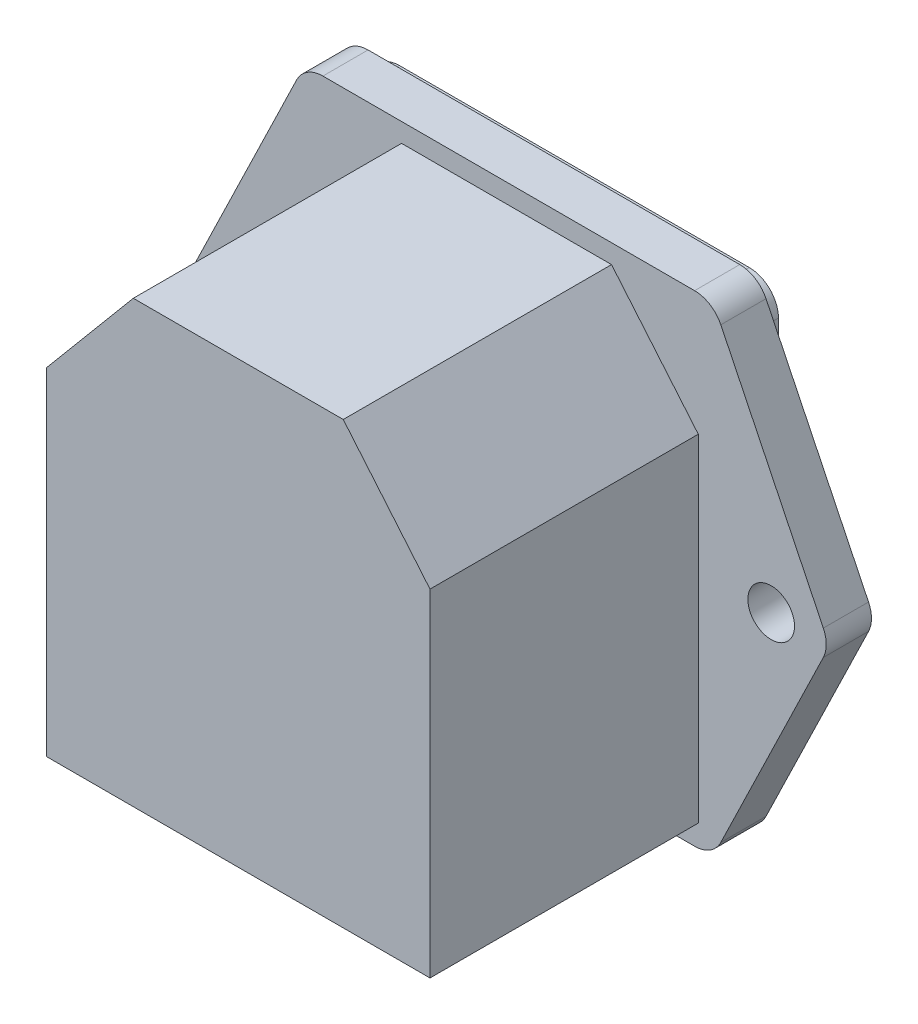
SolidWorks part; units mm, degrees
ref_plane "Front Plane" through (0, 0, 0) normal (0, 0, 1) x (1, 0, 0)
ref_plane "Top Plane" through (0, 0, 0) normal (0, 1, 0) x (1, 0, 0)
ref_plane "Right Plane" through (0, 0, 0) normal (1, 0, 0) x (0, 0, -1)
sketch "Sketch1" plane through (0, 0, 0) normal (0, 0, 1) x (1, 0, 0)
  line L1 (0, 0) -> (26.3, 0)
  line L2 (0, 0) -> (0, 30.2)
  line L3 (0, 30.2) -> (26.3, 30.2)
  line L4 (26.3, 0) -> (26.3, 30.2)
  dimension "D1" = 26.3
  dimension "D2" = 30.2
extrude "Boss-Extrude1" add sketch "Sketch1" along normal blind 21.5
sketch "Sketch2" plane through (0, 0, 21.5) normal (0, 0, 1) x (1, 0, 0)
  line L0 (0, 23.1) -> (26.3, 23.1)
  line L1 (0, 30.2) -> (0, 0) construction
  line L2 (26.3, 0) -> (26.3, 30.2) construction
  line L3 (26.3, 30.2) -> (0, 30.2) construction
  line L4 (13.15, 30.2) -> (13.15, 41.5338) construction
  line L5 (20.35, 30.2) -> (5.95, 30.2)
  line L6 (5.95, 30.2) -> (0, 23.1)
  line L7 (20.35, 30.2) -> (26.3, 23.1)
  line L9 (26.3, 23.1) -> (0, 23.1)
  line L10 (26.3, 23.1) -> (26.3, 30.2)
  line L11 (26.3, 30.2) -> (0, 30.2)
  line L12 (0, 23.1) -> (0, 30.2)
  line M7 (0, 30.2) -> (0, 0)
  line M9 (26.3, 0) -> (26.3, 30.2)
  line M10 (26.3, 30.2) -> (0, 30.2)
  dimension "D1" = 7.1
  dimension "D2" = 7.2
extrude "Cut-Extrude1" cut sketch "Sketch2" against normal blind 26 contours L6 M10 M7 | L7 M10 M9
sketch "Sketch3" plane through (0, 0, 0) normal (0, 0, -1) x (-1, 0, 0)
  line L0 (-26.3, 0) -> (-26.3, 23.1) construction
  line L1 (-35.3, -1.5) -> (8.7, -1.5)
  line L2 (-35.3, -1.5) -> (-35.3, 31.5)
  line L3 (-35.3, 31.5) -> (8.7, 31.5)
  line L4 (8.7, -1.5) -> (8.7, 31.5)
  line L5 (0, 0) -> (-26.3, 0) construction
  dimension "D1" = 33
  dimension "D2" = 44
  dimension "D3" = 9
  dimension "D4" = 1.5
extrude "Boss-Extrude2" add sketch "Sketch3" against normal blind 3.1
sketch "Sketch4" plane through (0, 0, 0) normal (0, 0, -1) x (-1, 0, 0)
  line L0 (-13.3, 31.5) -> (-13.3, 35.1997) construction
  line L1 (8.7, 31.5) -> (-35.3, 31.5) construction
  line L2 (0.7, 31.5) -> (-27.3, 31.5)
  line L3 (-35.3, 15) -> (-39.974, 15) construction
  line L4 (-35.3, 31.5) -> (-35.3, -1.5) construction
  line L5 (-27.3, 31.5) -> (-35.3, 15)
  line L6 (0.7, 31.5) -> (8.7, 15)
  line L7 (-27.3, -1.5) -> (-35.3, 15)
  line L8 (0.7, -1.5) -> (8.7, 15)
  line L9 (-13.3, -1.5) -> (-13.3, -5.1997) construction
  line L10 (0.7, -1.5) -> (-27.3, -1.5)
  line L12 (-35.3, 31.5) -> (8.7, 31.5)
  line L13 (-35.3, 31.5) -> (-35.3, -1.5)
  line L14 (-35.3, -1.5) -> (8.7, -1.5)
  line L15 (8.7, 31.5) -> (8.7, -1.5)
  line M6 (-35.3, 31.5) -> (-35.3, -1.5)
  line M7 (-35.3, -1.5) -> (8.7, -1.5)
  line M8 (8.7, -1.5) -> (8.7, 31.5)
  line M9 (8.7, 31.5) -> (-35.3, 31.5)
  dimension "D1" = 14
extrude "Cut-Extrude2" cut sketch "Sketch4" against normal blind 3.1 contours L5 M9 M6 | L6 M9 M8 | L8 M7 M8 | L7 M7 M6
fillet "Fillet1" radius 2 6 edges at (-0.7, -1.5, 1.55) (27.3, -1.5, 1.55) (27.3, 31.5, 1.55) (-0.7, 31.5, 1.55) (-8.7, 15, 1.55) (35.3, 15, 1.55)
sketch "Sketch5" plane through (0, 0, 0) normal (0, 0, -1) x (-1, 0, 0)
  line L0 (-13.3, 31.5) -> (-13.3, -1.5) construction
  line L1 (-0.553, 31.5) -> (-26.047, 31.5) construction
  line L2 (-26.047, -1.5) -> (-0.553, -1.5) construction
  line L4 (-35.0773, 15) -> (8.4773, 15) construction
  line L5 (-27.3, -0.25) -> (0.7, -0.25)
  line L6 (-27.3, -0.25) -> (-27.3, 30.25)
  line L7 (-27.3, 30.25) -> (0.7, 30.25)
  line L8 (0.7, -0.25) -> (0.7, 30.25)
  line L9 (-27.3, -0.25) -> (0.7, 30.25) construction
  line L10 (-27.3, 30.25) -> (0.7, -0.25) construction
  arc A0 (-34.8769, 15.8725) -> (-34.8769, 14.1275) centre (-33.0773, 15) ccw construction
  arc A1 (8.2769, 14.1275) -> (8.2769, 15.8725) centre (6.4773, 15) ccw construction
  point P14 (-13.3, 15)
  dimension "D1" = 28
  dimension "D2" = 30.5
extrude "Boss-Extrude3" add sketch "Sketch5" along normal blind 1.4
fillet "Fillet2" radius 2 4 edges at (-0.7, -0.25, -0.7) (27.3, -0.25, -0.7) (-0.7, 30.25, -0.7) (27.3, 30.25, -0.7)
sketch "Sketch6" plane through (0, 0, -1.4) normal (0, 0, -1) x (-1, 0, 0)
  line L0 (-27.3, 28.25) -> (-27.3, 1.75) construction
  line L1 (-1.3, 30.25) -> (-25.3, 30.25) construction
  line L2 (-25.3, 24.25) -> (-1.3, 24.25) construction
  line L3 (-25.3, 11.45) -> (-25.3, 28.45)
  line L4 (-25.3, 11.45) -> (-1.3, 11.45)
  line L5 (-25.3, 28.45) -> (-1.3, 28.45)
  line L6 (-1.3, 11.45) -> (-1.3, 28.45)
  line L7 (-1.3, 24.25) -> (-5.55, 28.45)
  line L8 (-25.3, 24.25) -> (-21.05, 28.45)
  line L9 (-13.3, 28.45) -> (-13.3, 32.8316) construction
  line L11 (-14.6737, 24.25) -> (-12.6737, 24.25)
  line L12 (-14.6737, 24.25) -> (-14.6737, 22.25)
  line L13 (-14.6737, 22.25) -> (-12.6737, 22.25)
  line L14 (-12.6737, 24.25) -> (-12.6737, 22.25)
  line L15 (-8.3, 19.45) -> (-6.3, 19.45)
  line L16 (-18.3, 17.45) -> (-20.3, 17.45)
  line L17 (-18.3, 17.45) -> (-18.3, 19.45)
  line L18 (-18.3, 19.45) -> (-20.3, 19.45)
  line L19 (-20.3, 17.45) -> (-20.3, 19.45)
  line L20 (-8.3, 19.45) -> (-8.3, 17.45)
  line L21 (-8.3, 17.45) -> (-6.3, 17.45)
  line L22 (-6.3, 19.45) -> (-6.3, 17.45)
  dimension "D1" = 24
  dimension "D2" = 17
  dimension "D3" = 2
  dimension "D4" = 1.8
  dimension "D5" = 7.75
  dimension "D6" = 4.2
  dimension "D7" = 2
  dimension "D8" = 2
  dimension "D9" = 2
  dimension "D10" = 2
  dimension "D11" = 2
  dimension "D12" = 2
  dimension "D13" = 6
  dimension "D14" = 6
  dimension "D15" = 12
  dimension "D16" = 5
extrude "Cut-Extrude3" cut sketch "Sketch6" against normal blind 20 contours L8 L3 L4 L6 L7 L5 L11 L14 L13 L12 L16 L19 L18 L17 L15 L22 L21 L20
sketch "Sketch7" plane through (0, 0, 0) normal (0, 0, -1) x (-1, 0, 0)
  line L0 (-35.0773, 15) -> (8.4773, 15) construction
  line L1 (-27.3, 28.25) -> (-27.3, 1.75) construction
  line L2 (0.7, 1.75) -> (0.7, 28.25) construction
  arc A0 (-34.8769, 15.8725) -> (-34.8769, 14.1275) centre (-33.0773, 15) ccw construction
  arc A1 (8.2769, 14.1275) -> (8.2769, 15.8725) centre (6.4773, 15) ccw construction
  circle A2 centre (-31.3, 15) radius 1.6
  circle A3 centre (4.7, 15) radius 1.6
  dimension "D1" = 3.2
  dimension "D2" = 3.2
  dimension "D3" = 4
  dimension "D4" = 4
extrude "Cut-Extrude4" cut sketch "Sketch7" against normal blind 20
